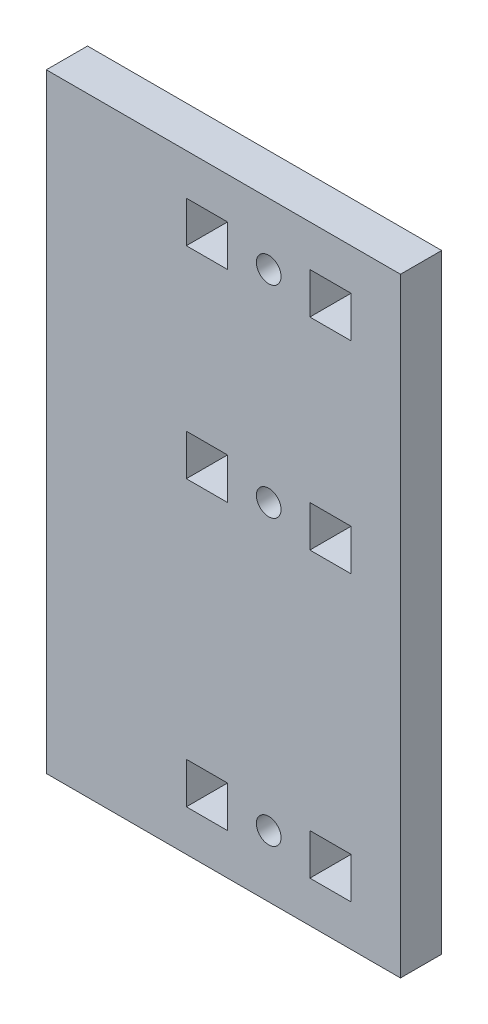
SolidWorks part; units mm, degrees
ref_plane "Front Plane" through (0, 0, 0) normal (0, 0, 1) x (1, 0, 0)
ref_plane "Top Plane" through (0, 0, 0) normal (0, 1, 0) x (1, 0, 0)
ref_plane "Right Plane" through (0, 0, 0) normal (1, 0, 0) x (0, 0, -1)
sketch "Sketch1" plane through (0, 0, 0) normal (0, 0, 1) x (1, 0, 0)
  line L0 (0, 0) -> (-6.7036, 0) construction
  line L1 (-27, -42) -> (16, -42)
  line L2 (-27, -42) -> (-27, 32)
  line L3 (-27, 32) -> (16, 32)
  line L4 (16, -42) -> (16, 32)
  line L7 (0, 0) -> (0, 72.9696) construction
  point P0 (0, 0)
  point P8 (0, 0)
  point P10 (0, 0)
  point P11 (0, 0)
  line B0 (-5, 2.5) -> (-10, 2.5)
  line B1 (-5, 2.5) -> (-5, -2.5)
  line B2 (-5, -2.5) -> (-10, -2.5)
  line B3 (-10, 2.5) -> (-10, -2.5)
  line B4 (5, 2.5) -> (10, 2.5)
  line B5 (5, 2.5) -> (5, -2.5)
  line B6 (5, -2.5) -> (10, -2.5)
  line B7 (10, 2.5) -> (10, -2.5)
  line B8 (0, 0) -> (0, 6.9724) construction
  circle B9 centre (0, 0) radius 1.5
  line B10 (-5, 27) -> (-10, 27)
  line B11 (-5, 27) -> (-5, 22)
  line B12 (-5, 22) -> (-10, 22)
  line B13 (-10, 27) -> (-10, 22)
  line B14 (5, 27) -> (10, 27)
  line B15 (5, 27) -> (5, 22)
  line B16 (5, 22) -> (10, 22)
  line B17 (10, 27) -> (10, 22)
  line B18 (0, 24.5) -> (0, 31.4724) construction
  circle B19 centre (0, 24.5) radius 1.5
  line B20 (-5, -32) -> (-10, -32)
  line B21 (-5, -32) -> (-5, -37)
  line B22 (-5, -37) -> (-10, -37)
  line B23 (-10, -32) -> (-10, -37)
  line B24 (5, -32) -> (10, -32)
  line B25 (5, -32) -> (5, -37)
  line B26 (5, -37) -> (10, -37)
  line B27 (10, -32) -> (10, -37)
  line B28 (0, -34.5) -> (0, -27.5276) construction
  circle B29 centre (0, -34.5) radius 1.5
  dimension "D1" = 34.5
  dimension "D2" = 24.5
  dimension "D3" = 7.5
  dimension "D4" = 7.5
  dimension "D5" = 16
  dimension "D6" = 27
sketch_block_instance "Trou M3 plots 5mm-1"
sketch_block "Trou M3 plots 5mm" parameters "D2"=3, "D1"=5, "D3"=5, "D4"=10
sketch_block_instance "Trou M3 plots 5mm-2"
sketch_block_instance "Trou M3 plots 5mm-3"
extrude "Boss-Extrude1" add sketch "Sketch1" along normal blind 5
